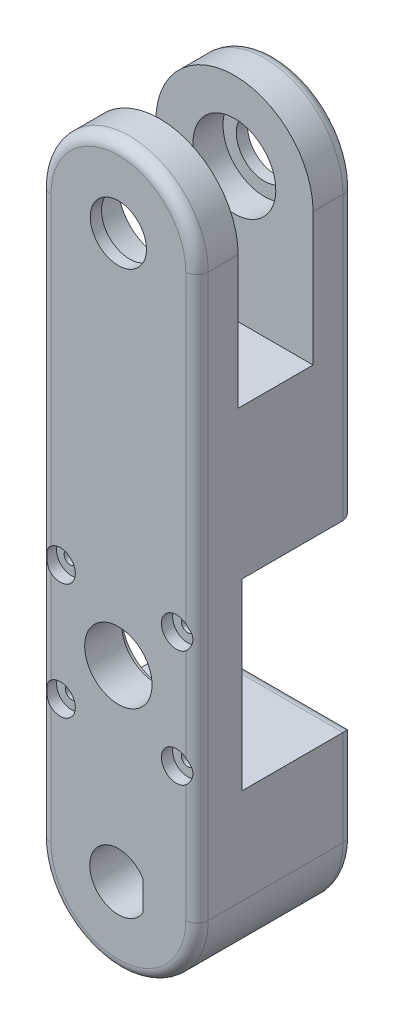
SolidWorks part; units mm, degrees
ref_plane "前视基准面" through (0, 0, 0) normal (0, 0, 1) x (1, 0, 0)
ref_plane "上视基准面" through (0, 0, 0) normal (0, 1, 0) x (1, 0, 0)
ref_plane "右视基准面" through (0, 0, 0) normal (1, 0, 0) x (0, 0, -1)
sketch "草图1" plane through (0, 0, 0) normal (0, 0, 1) x (1, 0, 0)
  line L0 (-21, 0) -> (-21, 150)
  line L2 (21, 150) -> (21, 0)
  arc A0 (-21, 0) -> (21, 0) centre (0, 0) ccw
  arc A1 (21, 150) -> (-21, 150) centre (0, 150) ccw
  dimension "D1" = 42
  dimension "D2" = 150
extrude "凸台-拉伸1" add sketch "草图1" along normal blind 42
sketch "草图2" plane through (0, 0, 0) normal (0, 0, -1) x (-1, 0, 0)
  line L0 (0, 0) -> (0, 150) construction
  circle A0 centre (0, 50) radius 9
  dimension "D1" = 18
  dimension "D2" = 50
extrude "切除-拉伸1" cut sketch "草图2" against normal through all
sketch "草图3" plane through (0, 0, 0) normal (0, 0, -1) x (-1, 0, 0)
  line L1 (25, 74.5) -> (-25, 74.5)
  line L2 (25, 74.5) -> (25, 25.5)
  line L3 (25, 25.5) -> (-25, 25.5)
  line L4 (-25, 74.5) -> (-25, 25.5)
  line L5 (25, 74.5) -> (-25, 25.5) construction
  line L6 (25, 25.5) -> (-25, 74.5) construction
  point P0 (0, 50)
  dimension "D1" = 49
  dimension "D2" = 50
extrude "切除-拉伸2" cut sketch "草图3" against normal blind 30
sketch "草图4" plane through (-21, 0, 0) normal (-1, 0, 0) x (0, 0, 1)
  line L0 (42, 150) -> (0, 150) construction
  line L1 (11, 114.5) -> (31, 114.5)
  line L2 (11, 114.5) -> (11, 185.5)
  line L3 (11, 185.5) -> (31, 185.5)
  line L4 (31, 114.5) -> (31, 185.5)
  line L5 (11, 114.5) -> (31, 185.5) construction
  line L6 (11, 185.5) -> (31, 114.5) construction
  line L7 (30, 74.5) -> (0, 74.5) construction
  point P0 (21, 150)
  dimension "D1" = 20
  dimension "D2" = 40
extrude "切除-拉伸3" cut sketch "草图4" against normal through all
sketch "草图5" plane through (0, 0, 42) normal (0, 0, 1) x (1, 0, 0)
  circle A0 centre (0, 150) radius 11.05
  dimension "D1" = 22.1
extrude "切除-拉伸4" cut sketch "草图5" against normal blind 10 from offset 3 offset against normal yes
fillet "圆角1" radius 3 4 edges at (-21, 75, 42) (0, 171, 42) (21, 75, 42) (0, -21, 42)
fillet "圆角2" radius 3 8 edges at (0, -21, 0) (21, 12.75, 0) (0, 25.5, 0) (-21, 12.75, 0) (0, 171, 0) (-21, 112.25, 0) (0, 74.5, 0) (21, 112.25, 0)
sketch "草图6" plane through (0, 0, 39) normal (0, 0, -1) x (-1, 0, 0)
  circle A0 centre (0, 150) radius 7.5
  dimension "D1" = 15
extrude "切除-拉伸5" cut sketch "草图6" against normal blind 10
ref_plane "基准面1" through (0, 0, 21) normal (0, 0, 1) x (1, 0, 0)
mirror "镜向1" about plane through (0, 0, 21) normal (0, 0, 1) of "切除-拉伸4", "切除-拉伸5"
sketch "草图8" plane through (0, 0, 30) normal (0, 0, -1) x (-1, 0, 0)
  circle A0 centre (-15.5, 34.5) radius 1.65
  circle A1 centre (-15.5, 65.5) radius 1.65
  circle A2 centre (15.8335, 65.5) radius 1.65
  circle A3 centre (15.5, 34.5) radius 1.65
  dimension "D1" = 3.3
extrude "切除-拉伸6" cut sketch "草图8" against normal through all
sketch "草图9" plane through (0, 0, 42) normal (0, 0, 1) x (1, 0, 0)
  circle A0 centre (15.5, 65.5) radius 4
  circle A1 centre (15.5, 34.5) radius 4
  circle A2 centre (-15.5, 65.5) radius 4
  circle A3 centre (-15.5, 34.5) radius 4
  dimension "D1" = 8
extrude "切除-拉伸7" cut sketch "草图9" against normal blind 3
ref_plane "基准面2" through (0, 0, 21) normal (0, 0, 1) x (1, 0, 0)
sketch "草图12" plane through (0, 0, 21) normal (0, 0, 1) x (1, 0, 0)
  point P0 (0, 0)
sketch "草图13" plane through (0, 0, 42) normal (0, 0, 1) x (1, 0, 0)
  line L0 (0, 7.65) -> (0, -7.65) construction
  line L1 (6.6, 3.8681) -> (6.6, -3.8681)
  circle A0 centre (0, 0) radius 7.65
  dimension "D1" = 15.3
  dimension "D2" = 6.6
extrude "切除-拉伸8" cut sketch "草图13" against normal through all both and the other way through all contours A0 L0 L1 | L0 A0
sketch "草图14" plane through (0, 0, 0) normal (0, 0, -1) x (-1, 0, 0)
  circle A0 centre (0, 0) radius 15.1
  dimension "D1" = 30.2
extrude "切除-拉伸9" cut sketch "草图14" against normal blind 10
sketch "草图15" plane through (0, 0, 30) normal (0, 0, -1) x (-1, 0, 0)
  circle A0 centre (0, 50) radius 11.1
  dimension "D1" = 22.2
extrude "切除-拉伸10" cut sketch "草图15" against normal blind 2.1
sketch "草图16" plane through (0, 0, 0) normal (1, 0, 0) x (0, 0, -1)
  point P0 (0, 75.5747)
